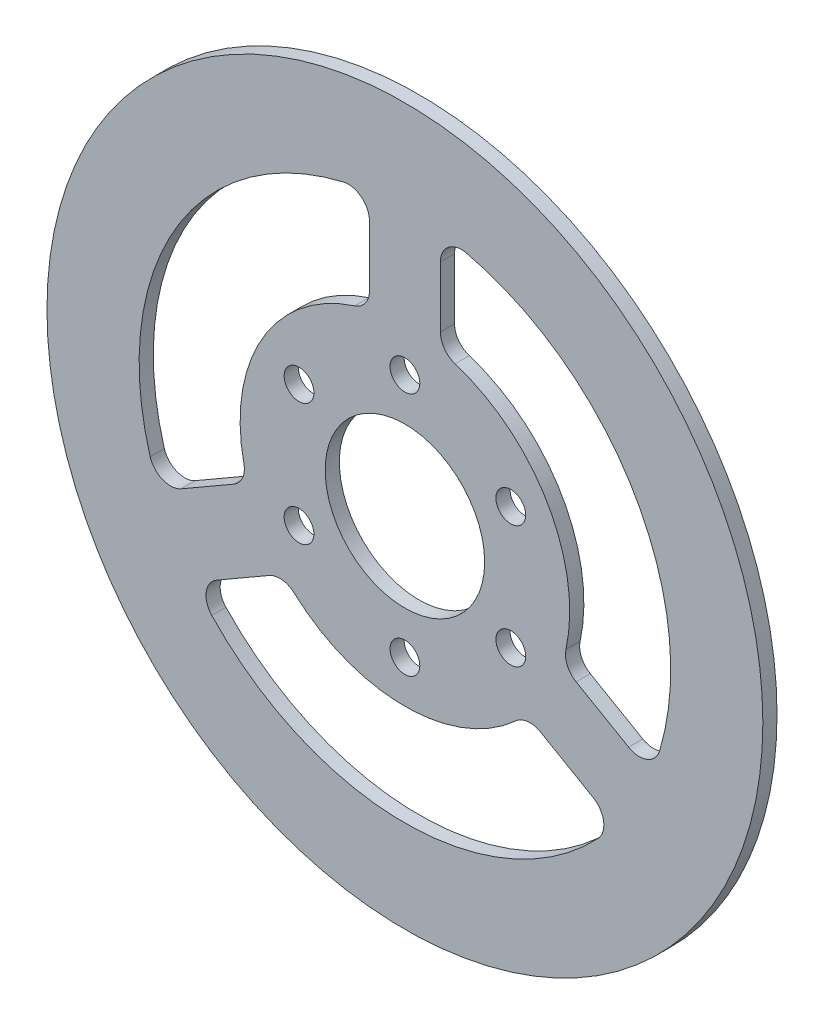
SolidWorks part; units mm, degrees
material "Thornel Mat VMA"
ref_plane "前视基准面" through (0, 0, 0) normal (0, 0, 1) x (1, 0, 0)
ref_plane "上视基准面" through (0, 0, 0) normal (0, 1, 0) x (1, 0, 0)
ref_plane "右视基准面" through (0, 0, 0) normal (1, 0, 0) x (0, 0, -1)
other "Configuration Table"
sketch "草图1" plane through (0, 0, 0) normal (0, 0, 1) x (1, 0, 0)
  circle A0 centre (0, 0) radius 50.5
  dimension "D1" = 101
extrude "凸台-拉伸1" add sketch "草图1" along normal blind 2
sketch "草图2" plane through (0, 0, 2) normal (0, 0, 1) x (1, 0, 0)
  line L0 (0, 37.5) -> (0, 23.25) construction
  line L1 (-5, 37.5) -> (-5, 22.706)
  line L2 (5, 37.5) -> (5, 22.706)
  line L3 (-5, 37.5) -> (-5, 23.25) construction
  line L4 (5, 37.5) -> (5, 23.25) construction
  line L5 (29.976, -23.0801) -> (17.164, -15.6831)
  line L6 (34.976, -14.4199) -> (22.164, -7.0229)
  line L7 (-34.976, -14.4199) -> (-22.164, -7.0229)
  line L8 (-29.976, -23.0801) -> (-17.164, -15.6831)
  circle A0 centre (0, 0) radius 17.25 construction
  circle A1 centre (0, 0) radius 11.25
  circle A2 centre (0, 0) radius 23.25
  circle A3 centre (0, 0) radius 37.5
  circle A4 centre (0, 17.25) radius 2.1
  circle A5 centre (14.9389, 8.625) radius 2.1
  circle A6 centre (14.9389, -8.625) radius 2.1
  circle A7 centre (0, -17.25) radius 2.1
  circle A8 centre (-14.9389, -8.625) radius 2.1
  circle A9 centre (-14.9389, 8.625) radius 2.1
  point P21 (0, 0)
  point P25 (27.0806, -11.3989)
  point P31 (0, 0)
  point P40 (0, 0)
  dimension "D1" = 34.5
  dimension "D2" = 6
  dimension "D3" = 4.2
  dimension "D4" = 6
  dimension "D5" = 6
  dimension "D6" = 75
  dimension "D7" = 5
  dimension "D8" = 5
  dimension "D9" = 3
extrude "切除-拉伸1" cut sketch "草图2" against normal blind 10 contours L1 A3 L7 A2 | L6 A3 L2 A2 | L8 A3 L5 A2 | A1 | A8 | A9 | A4 | A5 | A6 | A7
fillet "圆角1" radius 3 12 edges at (22.164, -7.0229, 1) (5, 22.706, 1) (34.686, -14.2525, 1) (-5, 22.706, 1) (-22.164, -7.0229, 1) (-34.686, -14.2525, 1) (-5, 37.1652, 1) (-17.164, -15.6831, 1) (17.164, -15.6831, 1) (29.686, -22.9127, 1) (-29.686, -22.9127, 1) (5, 37.1652, 1)
